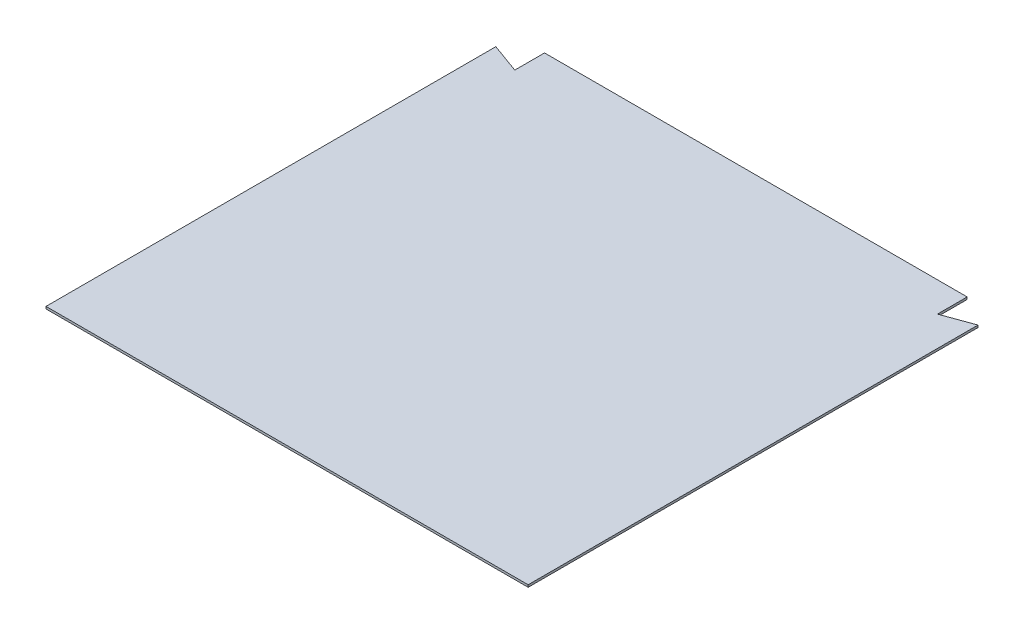
SolidWorks part; units mm, degrees
ref_plane "Front Plane" through (0, 0, 0) normal (0, 0, 1) x (1, 0, 0)
ref_plane "Top Plane" through (0, 0, 0) normal (0, 1, 0) x (1, 0, 0)
ref_plane "Right Plane" through (0, 0, 0) normal (1, 0, 0) x (0, 0, -1)
sketch "Sketch1" plane through (0, 0, 0) normal (0, 1, 0) x (1, 0, 0)
  line L1 (-142, -147.5) -> (142, -147.5)
  line L2 (-142, -147.5) -> (-142, 147.5)
  line L3 (-142, 147.5) -> (142, 147.5)
  line L4 (142, -147.5) -> (142, 147.5)
  line L5 (-142, -147.5) -> (142, 147.5) construction
  line L6 (-142, 147.5) -> (142, -147.5) construction
  point P0 (0, 0)
  dimension "D1" = 284
  dimension "D2" = 295
extrude "Boss-Extrude1" add sketch "Sketch1" along normal blind 1.5 contours L2 L3 L4 L1
sketch "Sketch9" plane through (-142, 0, 0) normal (-1, 0, 0) x (0, 0, 1)
  line L0 (-147.5, 1.5) -> (-147.5, 0) construction
  line L1 (147.5, 0) -> (-147.5, 0)
  line L2 (147.5, 0) -> (147.5, 1.5)
  line L3 (147.5, 1.5) -> (-147.5, 1.5)
  line L4 (-147.5, 0) -> (-147.5, 1.5)
  dimension "D1" = 1.5
extrude "Boss-Extrude9" add sketch "Sketch9" along normal blind 20
sketch "Sketch10" plane through (142, 0, 0) normal (1, 0, 0) x (0, 0, -1)
  line L0 (-147.5, 1.5) -> (-147.5, 0) construction
  line L1 (147.5, 0) -> (-147.5, 0)
  line L2 (147.5, 0) -> (147.5, 1.5)
  line L3 (147.5, 1.5) -> (-147.5, 1.5)
  line L4 (-147.5, 0) -> (-147.5, 1.5)
  dimension "D1" = 1.5
extrude "Boss-Extrude10" add sketch "Sketch10" along normal blind 20
sketch "Sketch13" plane through (0, 1.5, 0) normal (0, 1, 0) x (1, 0, 0)
  line L1 (142, 147.5) -> (-142, 147.5)
  line L2 (142, 147.5) -> (142, 167.5)
  line L3 (142, 167.5) -> (-142, 167.5)
  line L4 (-142, 147.5) -> (-142, 167.5)
  line L6 (-162, 147.5) -> (162, 147.5) construction
  point P6 (0, 167.5)
  dimension "D1" = 284
  dimension "D2" = 20
  dimension "D3" = 0
  dimension "D4" = 0
extrude "Boss-Extrude11" add sketch "Sketch13" against normal up to surface (1.5 mm away) up to face at (0, 0, 0)
sketch "Sketch14" plane through (0, 1.5, 0) normal (0, 1, 0) x (1, 0, 0)
  line L0 (142, 147.5) -> (162, 154.7794)
  line L1 (142, 147.5) -> (162, 147.5)
  line L2 (162, 147.5) -> (162, 154.7794)
  line L3 (-142, 147.5) -> (-162, 147.5)
  line L4 (-162, 147.5) -> (-142, 147.5) construction
  line L5 (-162, -147.5) -> (-162, 147.5) construction
  line L6 (-162, 147.5) -> (-162, 154.7794)
  line L7 (-162, 154.7794) -> (-142, 147.5)
  dimension "D1" = 20
  dimension "D2" = 20
extrude "Boss-Extrude12" add sketch "Sketch14" against normal up to surface (1.5 mm away) up to face at (0, 0, -78.75)
